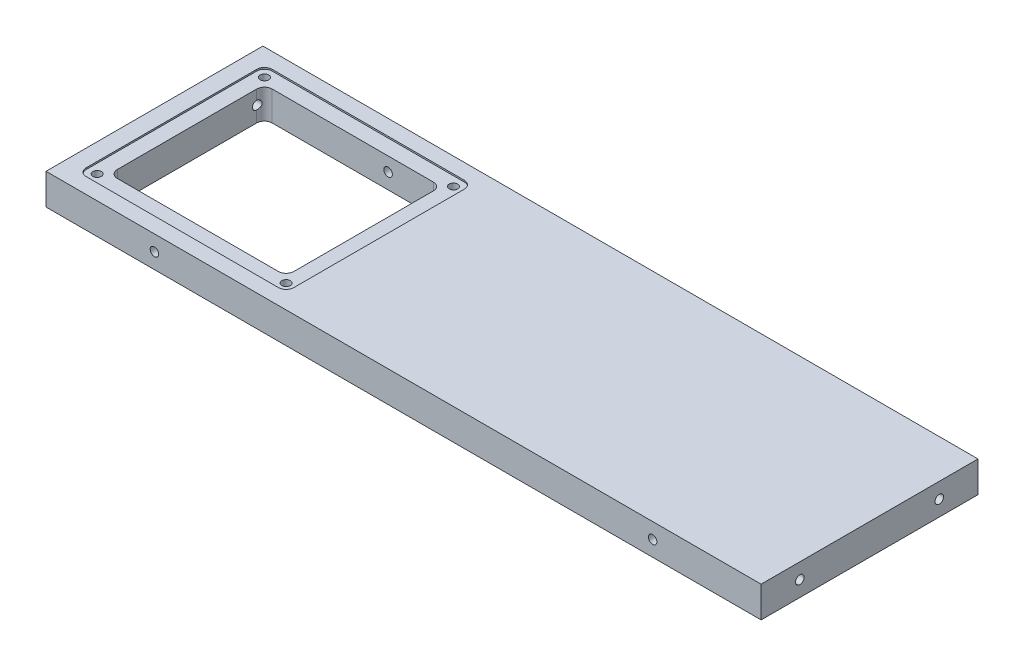
SolidWorks part; units mm, degrees
material "Oak"
ref_plane "Front Plane" through (0, 0, 0) normal (0, 0, 1) x (1, 0, 0)
ref_plane "Top Plane" through (0, 0, 0) normal (0, 1, 0) x (1, 0, 0)
ref_plane "Right Plane" through (0, 0, 0) normal (1, 0, 0) x (0, 0, -1)
sketch "Sketch1" plane through (0, 0, 0) normal (0, 0, 1) x (1, 0, 0)
  line L1 (-230.8028, 427) -> (230.8028, 427)
  line L2 (-230.8028, 427) -> (-230.8028, 407)
  line L3 (-230.8028, 407) -> (230.8028, 407)
  line L4 (230.8028, 427) -> (230.8028, 407)
  line L5 (-230.8028, 427) -> (230.8028, 427) construction
  dimension "D1" = 20
  dimension "D2" = 230.8028
  dimension "D3" = 461.6056
extrude "Boss-Extrude1" add sketch "Sketch1" along normal blind 140
sketch "Sketch2" plane through (0, 0, 140) normal (0, 0, 1) x (1, 0, 0)
  line L0 (-230.8028, 407) -> (230.8028, 407) construction
  line L1 (-55.8028, 419) -> (94.1972, 419)
  line L2 (-55.8028, 419) -> (-55.8028, 407)
  line L3 (-55.8028, 407) -> (94.1972, 407)
  line L4 (94.1972, 419) -> (94.1972, 407)
  line L5 (-55.8028, 419) -> (94.1972, 407) construction
  line L6 (-55.8028, 407) -> (94.1972, 419) construction
  line L7 (-230.8028, 427) -> (-230.8028, 407) construction
  point P0 (19.1972, 413)
  dimension "D1" = 12
  dimension "D2" = 150
  dimension "D3" = 250
extrude "Cut-Extrude1" cut sketch "Sketch2" against normal blind 80
sketch "Sketch3" plane through (0, 407, 0) normal (0, -1, 0) x (1, 0, 0)
  line L0 (-229.8028, 15) -> (-229.8028, 105) construction
  line L1 (-100.8028, 20) -> (-204.8028, 20)
  line L2 (-95.8028, 25) -> (-95.8028, 115)
  line L3 (-100.8028, 120) -> (-204.8028, 120)
  line L4 (-209.8028, 25) -> (-209.8028, 115)
  line L5 (-230.8028, 140) -> (-230.8028, 0) construction
  line L7 (-230.8028, 0) -> (230.8028, 0) construction
  line L8 (-230.8028, 140) -> (-55.8028, 140) construction
  arc A0 (-95.8028, 115) -> (-100.8028, 120) centre (-100.8028, 115) ccw
  arc A1 (-204.8028, 120) -> (-209.8028, 115) centre (-204.8028, 115) ccw
  arc A2 (-204.8028, 20) -> (-209.8028, 25) centre (-204.8028, 25) cw
  arc A3 (-100.8028, 20) -> (-95.8028, 25) centre (-100.8028, 25) ccw
  dimension "D5" = 5
  dimension "D1" = 20
  dimension "D2" = 20
  dimension "D3" = 20
  dimension "D4" = 135
extrude "Cut-Extrude2" cut sketch "Sketch3" against normal through all
sketch "Sketch4" plane through (0, 427, 0) normal (0, 1, 0) x (1, 0, 0)
  line L0 (-209.8028, -115) -> (-209.8028, -25) construction
  line L1 (-90.8028, -130) -> (-214.8028, -130)
  line L2 (-85.8028, -125) -> (-85.8028, -15)
  line L3 (-90.8028, -10) -> (-214.8028, -10)
  line L4 (-219.8028, -125) -> (-219.8028, -15)
  line L5 (-204.8028, -20) -> (-100.8028, -20) construction
  line L6 (-95.8028, -25) -> (-95.8028, -115) construction
  line L7 (-100.8028, -120) -> (-204.8028, -120) construction
  arc A1 (-85.8028, -15) -> (-90.8028, -10) centre (-90.8028, -15) ccw
  arc A2 (-214.8028, -10) -> (-219.8028, -15) centre (-214.8028, -15) ccw
  arc A3 (-214.8028, -130) -> (-219.8028, -125) centre (-214.8028, -125) cw
  arc A4 (-90.8028, -130) -> (-85.8028, -125) centre (-90.8028, -125) ccw
  dimension "D5" = 5
  dimension "D1" = 10
  dimension "D2" = 10
  dimension "D3" = 10
  dimension "D4" = 10
extrude "Cut-Extrude3" cut sketch "Sketch4" against normal blind 1
sketch "Sketch5" plane through (0, 426, 0) normal (0, 1, 0) x (1, 0, 0)
  line L0 (-100.8028, -120) -> (-204.8028, -120) construction
  line L1 (-95.8028, -25) -> (-95.8028, -115) construction
  line L2 (-152.8028, -130) -> (-152.8028, -10) construction
  line L3 (-214.8028, -130) -> (-90.8028, -130) construction
  line L4 (-90.8028, -10) -> (-214.8028, -10) construction
  line L5 (-85.8028, -70) -> (-219.8028, -70) construction
  line L6 (-85.8028, -125) -> (-85.8028, -15) construction
  line L7 (-219.8028, -15) -> (-219.8028, -125) construction
  circle A0 centre (-91.8028, -124) radius 2.75
  circle A1 centre (-213.8028, -124) radius 2.75
  circle A2 centre (-213.8028, -16) radius 2.75
  circle A3 centre (-91.8028, -16) radius 2.75
  dimension "D1" = 5.5
  dimension "D2" = 4
  dimension "D3" = 4
extrude "Cut-Extrude4" cut sketch "Sketch5" against normal blind 12
fillet "Fillet1" radius 5 2 edges at (94.1972, 413, 60) (-55.8028, 413, 60)
sketch "Sketch7" plane through (-230.8028, 0, 0) normal (-1, 0, 0) x (0, 0, 1)
  line L0 (70, 427) -> (70, 371.0072) construction
  line L1 (140, 427) -> (0, 427) construction
  circle A0 centre (25, 417) radius 2.75
  circle A1 centre (115, 417) radius 2.75
  dimension "D2" = 5.5
  dimension "D1" = 10
  dimension "D3" = 90
extrude "Cut-Extrude6" cut sketch "Sketch7" against normal blind 30
mirror "Mirror1" about plane through (0, 0, 0) normal (1, 0, 0) of "Cut-Extrude6"
sketch "Sketch8" plane through (0, 0, 140) normal (0, 0, 1) x (1, 0, 0)
  line L0 (0, 0) -> (0, 578.4164) construction
  line L1 (-230.8028, 407) -> (-55.8028, 407) construction
  line L2 (-230.8028, 427) -> (-230.8028, 407) construction
  circle A0 centre (-160.8028, 417) radius 2.75
  circle A1 centre (160.8028, 417) radius 2.75
  dimension "D2" = 5.5
  dimension "D1" = 10
  dimension "D3" = 70
extrude "Cut-Extrude7" cut sketch "Sketch8" against normal blind 30
sketch "Sketch9" plane through (0, 419, 0) normal (0, -1, 0) x (1, 0, 0)
  line L4 (-50.8028, 60) -> (89.1972, 60)
  line L5 (94.1972, 65) -> (94.1972, 140)
  line L6 (94.1972, 140) -> (-55.8028, 140)
  line L7 (-55.8028, 140) -> (-55.8028, 65)
  line L9 (94.1972, 65) -> (94.1972, 140)
  line L10 (94.1972, 140) -> (-55.8028, 140)
  line L11 (-55.8028, 140) -> (-55.8028, 65)
  line L12 (-50.8028, 60) -> (89.1972, 60)
  arc A2 (89.1972, 60) -> (94.1972, 65) centre (89.1972, 65) ccw
  arc A6 (89.1972, 60) -> (94.1972, 65) centre (89.1972, 65) ccw
  arc A7 (-55.8028, 65) -> (-50.8028, 60) centre (-50.8028, 65) ccw
  arc A9 (-55.8028, 65) -> (-50.8028, 60) centre (-50.8028, 65) ccw
  dimension "D1" = 0
extrude "Boss-Extrude2" add sketch "Sketch9" along normal up to surface (12 mm away) up to face at (-152.8028, 407, 70)
sketch "Sketch10" plane through (0, 407, 0) normal (0, -1, 0) x (1, 0, 0)
  line L0 (-85, 131) -> (-85, 121) construction
  line L1 (-85, 91) -> (-85, 81) construction
  line L2 (60, 131) -> (60, 121) construction
  line L3 (60, 91) -> (60, 81) construction
  arc A0 (-82.75, 128.75) -> (-87.25, 128.75) centre (-85, 128.75) ccw construction
  arc A1 (-87.25, 123.25) -> (-82.75, 123.25) centre (-85, 123.25) ccw construction
  arc A2 (-82.75, 88.75) -> (-87.25, 88.75) centre (-85, 88.75) ccw construction
  arc A3 (-87.25, 83.25) -> (-82.75, 83.25) centre (-85, 83.25) ccw construction
  arc A4 (62.25, 128.75) -> (57.75, 128.75) centre (60, 128.75) ccw construction
  arc A5 (57.75, 123.25) -> (62.25, 123.25) centre (60, 123.25) ccw construction
  arc A6 (62.25, 88.75) -> (57.75, 88.75) centre (60, 88.75) ccw construction
  arc A7 (57.75, 83.25) -> (62.25, 83.25) centre (60, 83.25) ccw construction
  circle A8 centre (-85, 126) radius 2.75
  circle A9 centre (-85, 86) radius 2.75
  circle A10 centre (60, 126) radius 2.75
  circle A11 centre (60, 86) radius 2.75
  dimension "D1" = 5.5
extrude "Cut-Extrude8" cut sketch "Sketch10" against normal blind 12
sketch "Sketch6" plane through (0, 407, 0) normal (0, -1, 0) x (1, 0, 0)
  line L0 (200.8028, 120) -> (76.8028, 120)
  line L2 (56.8028, 70) -> (-80.8028, 70)
  line L3 (-85.8028, 65) -> (-85.8028, 25)
  line L4 (-80.8028, 20) -> (56.8028, 20)
  line L5 (205.8028, 25) -> (205.8028, 115)
  line L6 (-230.8028, 140) -> (230.8028, 140) construction
  line L7 (-230.8028, 0) -> (230.8028, 0) construction
  line L9 (230.8028, 140) -> (230.8028, 0) construction
  line L12 (71.8028, 115) -> (71.8028, 25)
  line L13 (61.8028, 65) -> (61.8028, 25)
  line L14 (76.8028, 20) -> (200.8028, 20)
  line L15 (-95.8028, 25) -> (-95.8028, 115) construction
  arc A0 (200.8028, 20) -> (205.8028, 25) centre (200.8028, 25) ccw
  arc A1 (200.8028, 120) -> (205.8028, 115) centre (200.8028, 115) cw
  arc A3 (-80.8028, 70) -> (-85.8028, 65) centre (-80.8028, 65) ccw
  arc A4 (-85.8028, 25) -> (-80.8028, 20) centre (-80.8028, 25) ccw
  arc A5 (71.8028, 25) -> (76.8028, 20) centre (76.8028, 25) ccw
  arc A6 (61.8028, 65) -> (56.8028, 70) centre (56.8028, 65) ccw
  arc A7 (61.8028, 25) -> (56.8028, 20) centre (56.8028, 25) cw
  arc A8 (76.8028, 120) -> (71.8028, 115) centre (76.8028, 115) ccw
  point P33 (71.8028, 20)
  dimension "D6" = 5
  dimension "D8" = 5
  dimension "D10" = 5
  dimension "D11" = 5
  dimension "D1" = 20
  dimension "D2" = 20
  dimension "D3" = 134
  dimension "D4" = 25
  dimension "D5" = 50
  dimension "D7" = 10
  dimension "D9" = 10
extrude "Cut-Extrude5" cut sketch "Sketch6" against normal blind 14
sketch "Sketch11" plane through (0, 0, 0) normal (0, 0, -1) x (-1, 0, 0)
  line L0 (0, 0) -> (0, 533.1777) construction
  line L1 (-191.2125, 0) -> (191.2125, 0) construction
  line L3 (-230.8028, 427) -> (230.8028, 427) construction
  circle A0 centre (130, 417) radius 2.75
  circle A1 centre (-130, 417) radius 2.75
  dimension "D1" = 10
  dimension "D2" = 260
  dimension "D3" = 260
  dimension "D4" = 5.5
extrude "Cut-Extrude9" cut sketch "Sketch11" against normal blind 30
